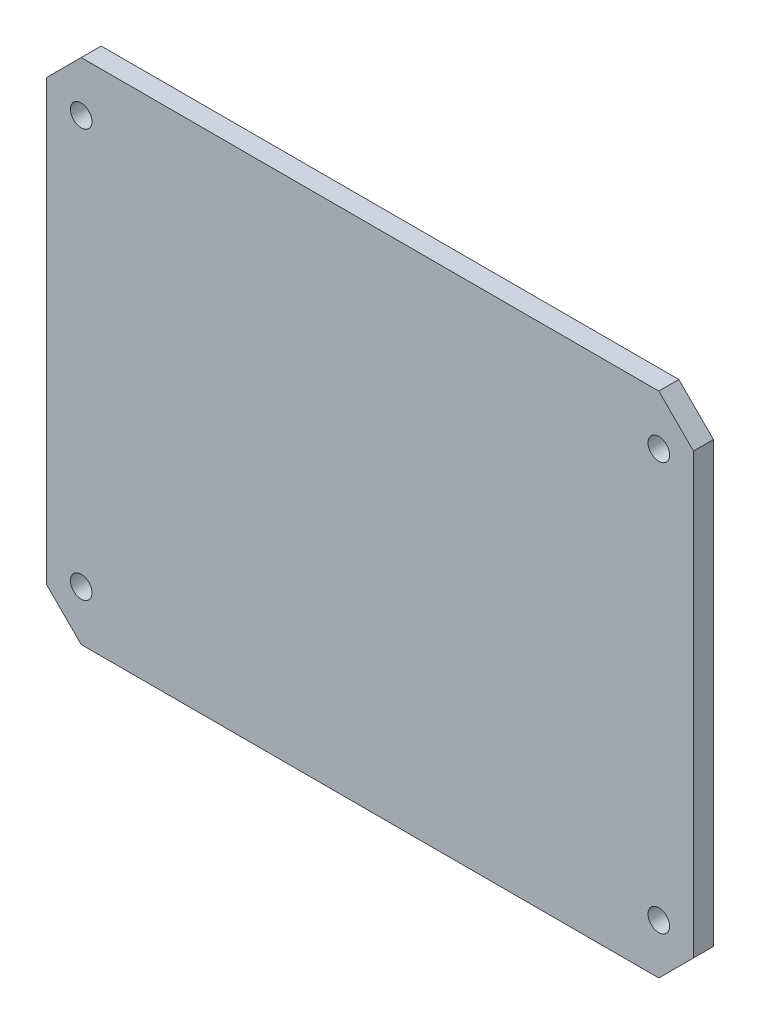
SolidWorks part; units mm, degrees
ref_plane "前视基准面" through (0, 0, 0) normal (0, 0, 1) x (1, 0, 0)
ref_plane "上视基准面" through (0, 0, 0) normal (0, 1, 0) x (1, 0, 0)
ref_plane "右视基准面" through (0, 0, 0) normal (1, 0, 0) x (0, 0, -1)
other "Configuration Table"
sketch "84 x 66 cover - four D2.8 holes profile" plane through (0, 0, 0) normal (0, 0, 1) x (1, 0, 0)
  line L0 (-37.5, -33) -> (37.5, -33)
  line L1 (37.5, -33) -> (42, -28.5)
  line L2 (42, -28.5) -> (42, 28.5)
  line L3 (42, 28.5) -> (37.5, 33)
  line L4 (37.5, 33) -> (-37.5, 33)
  line L5 (-37.5, 33) -> (-42, 28.5)
  line L6 (-42, 28.5) -> (-42, -28.5)
  line L7 (-42, -28.5) -> (-37.5, -33)
  circle A0 centre (-37.5, -26.5) radius 1.4
  circle A1 centre (37.5, -26.5) radius 1.4
  circle A2 centre (-37.5, 26.5) radius 1.4
  circle A3 centre (37.5, 26.5) radius 1.4
extrude "84 x 66 cover - four D2.8 holes" add sketch "84 x 66 cover - four D2.8 holes profile" along normal blind 2.6
